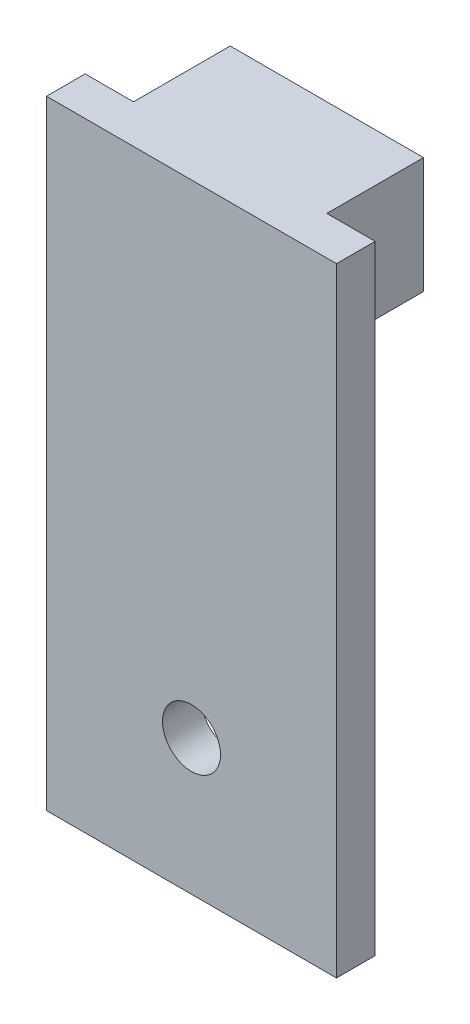
SolidWorks part; units mm, degrees
ref_plane "前视基准面" through (0, 0, 0) normal (0, 0, 1) x (1, 0, 0)
ref_plane "上视基准面" through (0, 0, 0) normal (0, 1, 0) x (1, 0, 0)
ref_plane "右视基准面" through (0, 0, 0) normal (1, 0, 0) x (0, 0, -1)
sketch "草图1" plane through (0, 0, 0) normal (0, 0, 1) x (1, 0, 0)
  line L1 (-7.5, 16) -> (7.5, 16)
  line L2 (-7.5, 16) -> (-7.5, -16)
  line L3 (-7.5, -16) -> (7.5, -16)
  line L4 (7.5, 16) -> (7.5, -16)
  line L5 (-7.5, 16) -> (7.5, -16) construction
  line L6 (-7.5, -16) -> (7.5, 16) construction
  point P0 (0, 0)
extrude "凸台-拉伸1" add sketch "草图1" along normal blind 2
sketch "草图2" plane through (0, 0, 0) normal (0, 0, -1) x (-1, 0, 0)
  line L0 (-7.5, 16) -> (7.5, 16) construction
  line L2 (-5, 16) -> (-5, 10)
  line L3 (-5, 10) -> (5, 10)
  line L4 (5, 16) -> (5, 10)
  line L7 (-5, 16) -> (5, 16)
  point P0 (0, 16)
extrude "凸台-拉伸2" add sketch "草图2" along normal blind 6
chamfer "倒角1" distance 1 angle 45 4 edges at (0, 10, -6) (-5, 13, -6) (0, 16, -6) (5, 13, -6)
sketch "草图3" plane through (0, 0, 2) normal (0, 0, 1) x (1, 0, 0)
  line L0 (0, 16) -> (0, -9)
  line L1 (7.5, 16) -> (-7.5, 16) construction
  circle A0 centre (0, -9) radius 1.5
extrude "切除-拉伸1" cut sketch "草图3" against normal blind 28
